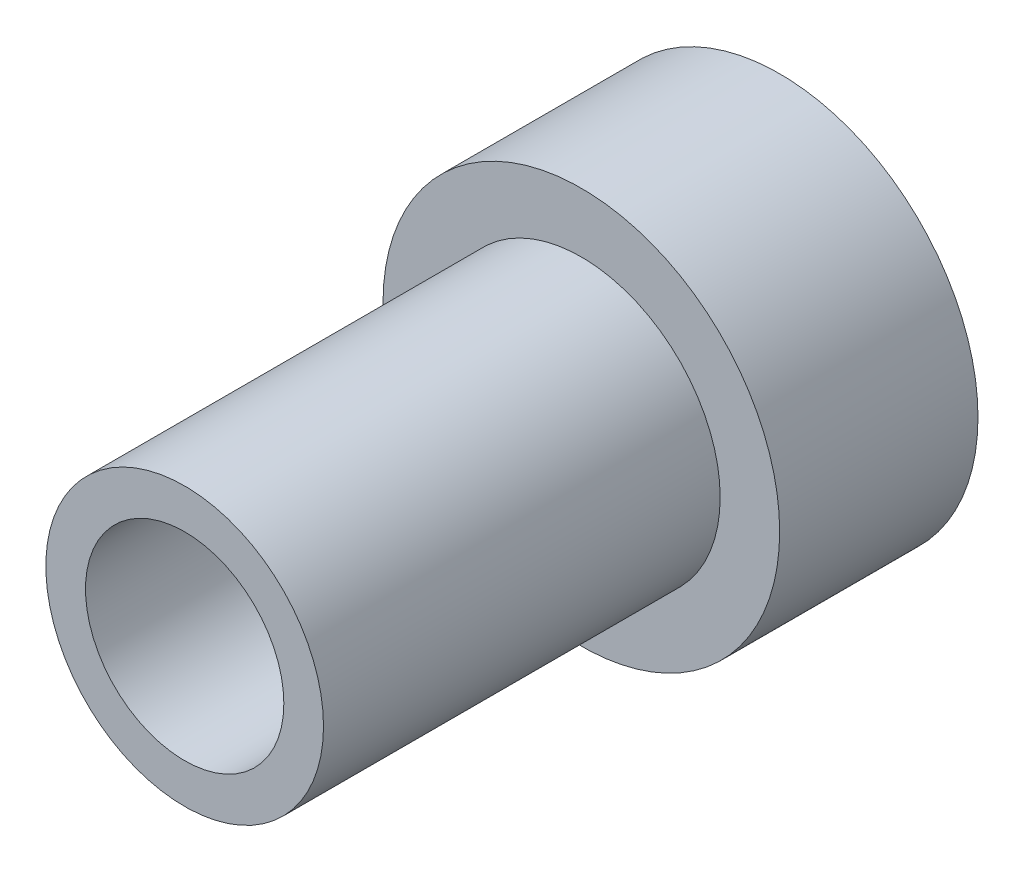
SolidWorks part; units mm, degrees
ref_plane "Front Plane" through (0, 0, 0) normal (0, 0, 1) x (1, 0, 0)
ref_plane "Top Plane" through (0, 0, 0) normal (0, 1, 0) x (1, 0, 0)
ref_plane "Right Plane" through (0, 0, 0) normal (1, 0, 0) x (0, 0, -1)
sketch "Sketch1" plane through (0, 0, 0) normal (0, 0, 1) x (1, 0, 0)
  circle A0 centre (0, 0) radius 5
  dimension "D1" = 10
extrude "Boss-Extrude1" add sketch "Sketch1" along normal blind 5
sketch "Sketch2" plane through (0, 0, 5) normal (0, 0, 1) x (1, 0, 0)
  circle A0 centre (0, 0) radius 3.5
  dimension "D1" = 7
extrude "Boss-Extrude2" add sketch "Sketch2" along normal blind 10
sketch "Sketch3" plane through (0, 0, 15) normal (0, 0, 1) x (1, 0, 0)
  circle A0 centre (0, 0) radius 2.5
  dimension "D1" = 5
extrude "Cut-Extrude1" cut sketch "Sketch3" against normal through all
